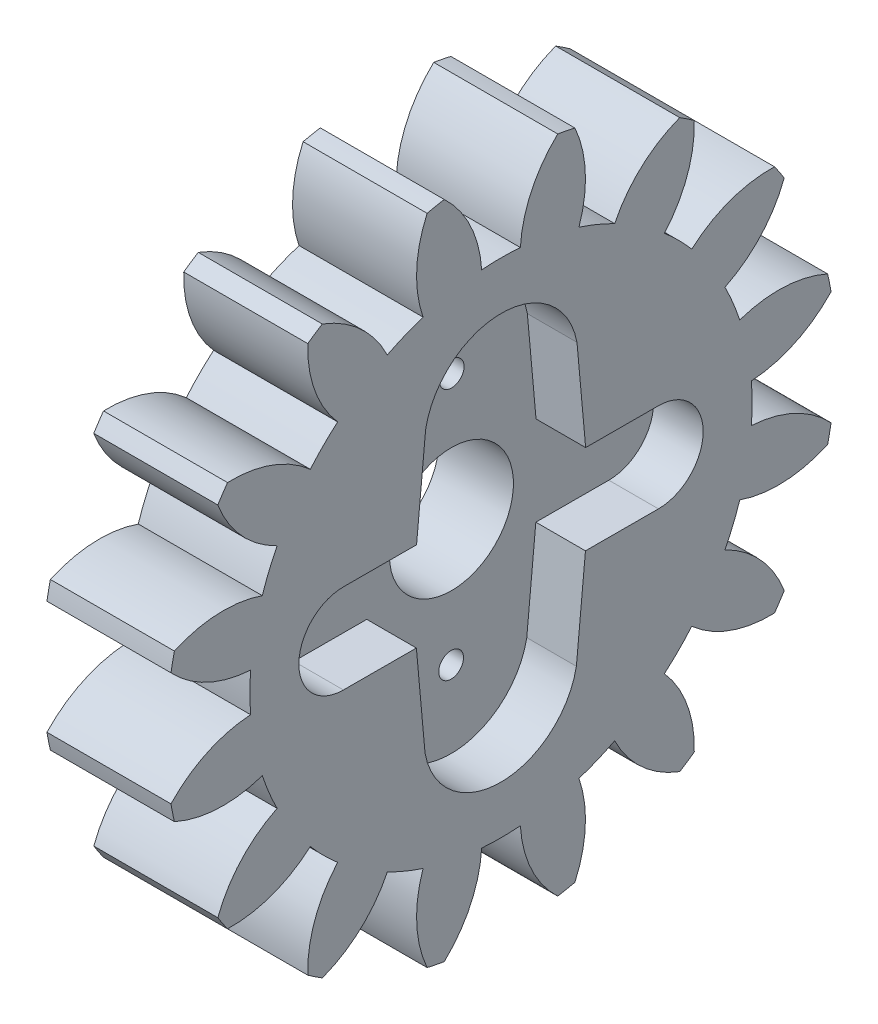
SolidWorks part; units mm, degrees
ref_plane "Plane1" through (0, 0, 0) normal (0, 0, 1) x (1, 0, 0)
ref_plane "Plane2" through (0, 0, 0) normal (0, 1, 0) x (1, 0, 0)
ref_plane "Plane3" through (0, 0, 0) normal (1, 0, 0) x (0, 0, -1)
other "Configuration Table"
sketch "HoldingSke" plane through (0, 0, 0) normal (0, 1, 0) x (1, 0, 0)
  line L0 (0, 0) -> (0.6408, -0.1838)
  line L1 (-15, 0) -> (100, 0) construction
  line L2 (0, 0) -> (-2.1039, 2.3779)
  line L3 (0, 0) -> (-11.863, 4.5341)
  line L4 (0, 0) -> (8.3015, 2.3804)
  line L5 (0, 0) -> (-46.8476, -17.4728)
  line L6 (0, 0) -> (-4.1448, -2.7965)
  line L7 (-2.1039, 2.3779) -> (8.6586, 51.2059)
  line L8 (-76.2, 54.61) -> (-75.3, 54.61)
  line L9 (-71.009, 38.7566) -> (-53.1078, 45.2721)
  line L10 (-76.2, 71.12) -> (104.1128, 71.12)
  line L11 (0, 0) -> (-5, 0)
  line L12 (-76.2, 101.6) -> (-76.147, 101.6)
  line L13 (24.9733, 27.94) -> (52.9518, 28.4284)
  line L14 (24.9733, 27.94) -> (24.9743, 27.94)
  line L15 (24.9733, 27.94) -> (100.4006, 29.5858)
  line L16 (-63.627, -1.5) -> (-12.827, -1.5)
  circle A0 centre (0, 0) radius 2.5
  circle A1 centre (0, 0) radius 10.124
  circle A2 centre (0, 0) radius 37.5
  circle A3 centre (0, 0) radius 2.5
  dimension "MHD" = 20.248
  dimension "Hub_dia" = 75
  dimension "Bore" = 5
  dimension "MBD" = 5
  dimension "Num_teeth" = 16
  dimension "Pitch" = 0.6667
  dimension "Overall_len" = 50
  dimension "Show_teeth" = 16
  dimension "Thickness" = 5
  dimension "OAL" = 50.0001
  dimension "T_dim" = 0.9
  dimension "Ap" = 20
  dimension "H" = 19.05
  dimension "Pitch_radius" = 180.3128
  dimension "Width" = 5
  dimension "Backlash" = 0.053
  dimension "Addendum_fac" = 1
  dimension "Dedendum_fac" = 1.25
  dimension "Clearance_fac" = 0.25
  dimension "Dedendum_add" = 0.001
  dimension "Module" = 1.5
sketch "BasProSke" plane through (0, 0, 0) normal (0, 1, 0) x (1, 0, 0)
  line L0 (-10, 0) -> (60, 0) construction
  line L1 (0, 0) -> (0, 13.5)
  line L2 (0, 0) -> (5, 0)
  line L3 (5, 0) -> (5, 13.5)
  line L4 (5, 13.5) -> (0, 13.5)
  dimension "Thickness" = 5
  dimension "Diameter" = 27
revolve "Base-Revolve" add sketch "BasProSke" angle 360 about L0
sketch "TooCutSke" plane through (0, 0, 0) normal (1, 0, 0) x (0, 0, -1)
  line L1 (0, 0) -> (0, 107) construction
  line L2 (0, 0) -> (-1.2689, 11.9327) construction
  line L3 (0, 0) -> (-4.663, 23.4427) construction
  line L4 (-1.2689, 11.9327) -> (-2.3315, 11.7214) construction
  arc A0 (0.7798, 10.0939) -> (-0.7798, 10.0939) centre (0, 0) ccw
  arc A1 (2.3105, 13.3266) -> (-2.3105, 13.3266) centre (0, 0) ccw
  circle A2 centre (0, 0) radius 12 construction
  circle A3 centre (0, 0) radius 11.2763 construction
  arc A4 (-0.7798, 10.0939) -> (-2.3105, 13.3266) centre (-5.571, 9.804) ccw
  arc A5 (2.3105, 13.3266) -> (0.7798, 10.0939) centre (5.571, 9.804) ccw
  dimension "Root_dia" = 20.248
  dimension "Overcut_dia" = 27.0508
  dimension "Pitch_dia" = 24
  dimension "Base_dia" = 22.5526
  dimension "Flank_rad" = 4.8
  dimension "Half_ang" = 11.25
  dimension "Half_CT" = 1.0835
extrude "ToothCut" cut sketch "TooCutSke" along normal through all
fillet "Breaks" [suppressed] radius 0.03
fillet "RootFillets" [suppressed] radius 0.376
pattern_circular "TeethCuts" count 16 every 22.5 about axis through (-10, 0, 0) along (1, 0, 0) of "ToothCut", "RootFillets", "Breaks"
sketch "HubNeaOneSke" plane through (0, 0, 0) normal (-1, 0, 0) x (0, 0, 1)
  circle A0 centre (0, 0) radius 10.124
  dimension "Diameter" = 20.248
extrude "HubNearOne" [suppressed] add sketch "HubNeaOneSke" along normal blind 45.0001
sketch "HubNeaBotSke" plane through (0, 0, 0) normal (-1, 0, 0) x (0, 0, 1)
  circle A0 centre (0, 0) radius 10.124
  dimension "Diameter" = 20.248
extrude "HubNearBoth" [suppressed] add sketch "HubNeaBotSke" along normal blind 22.5
ref_plane "FarPln" through (5, 0, 0) normal (1, 0, 0) x (0, 0, -1)
sketch "HubFarSke" plane through (5, 0, 0) normal (1, 0, 0) x (0, 0, -1)
  circle A0 centre (0, 0) radius 10.124
  dimension "Diameter" = 20.248
extrude "HubFar" [suppressed] add sketch "HubFarSke" along normal blind 22.5
sketch "BorSke" plane through (0, 0, 0) normal (1, 0, 0) x (0, 0, -1)
  circle A0 centre (0, 0) radius 2.5
  dimension "Diameter" = 5
extrude "Bore" cut sketch "BorSke" along normal mid plane 100.0001
sketch "KeySke" plane through (0, 0, 0) normal (1, 0, 0) x (0, 0, -1)
  line L0 (-1, 0) -> (-1, 3.4)
  line L1 (-1, 3.4) -> (1, 3.4)
  line L2 (1, 3.4) -> (1, 0)
  line L3 (0, 0) -> (0, 34) construction
  line L4 (-1, 0) -> (1, 0)
  dimension "Offset" = 3.4
  dimension "Width" = 2
extrude "Keyway" [suppressed] cut sketch "KeySke" along normal mid plane 100.0001
pattern_circular "Keyway2" [suppressed] count 2 every 90 about axis through (-10, 0, 0) along (1, 0, 0)
sketch "Esquisse1" plane through (5, 0, 0) normal (1, 0, 0) x (0, 0, -1)
  line L0 (-6.3538, -1.7865) -> (-3.4117, -1.7927) construction
  line L1 (-6.3538, -1.7865) -> (-3.4117, -1.7927)
  line L2 (-6.3462, 1.8135) -> (-3.404, 1.8073)
  line L3 (-3.4117, -1.7927) -> (-3.0624, -5.6432)
  line L4 (3.0384, -5.6562) -> (3.404, -1.8073)
  line L5 (3.404, -1.8073) -> (6.3462, -1.8135)
  line L6 (6.3538, 1.7865) -> (3.4117, 1.7927)
  line L7 (3.0624, 5.6432) -> (3.4117, 1.7927) construction
  line L8 (6.3538, 1.7865) -> (3.4117, 1.7927) construction
  line L9 (3.4117, 1.7927) -> (3.0624, 5.6432)
  line L10 (-3.404, 1.8073) -> (-3.0384, 5.6562)
  arc A0 (-6.3538, -1.7865) -> (-6.3462, 1.8135) centre (-6.35, 0.0135) cw
  arc A1 (-6.3462, 1.8135) -> (-6.3538, -1.7865) centre (-6.35, 0.0135) ccw construction
  arc A2 (-3.0624, -5.6432) -> (3.0384, -5.6562) centre (-0.0108, -5.0783) ccw
  arc A3 (6.3462, -1.8135) -> (6.3538, 1.7865) centre (6.35, -0.0135) ccw
  arc A4 (-3.0384, 5.6562) -> (3.0624, 5.6432) centre (0.0108, 5.0783) cw
extrude "Enlèv. mat.-Extru.1" cut sketch "Esquisse1" against normal blind 2
sketch "Esquisse2" plane through (3, 0, 0) normal (1, 0, 0) x (0, 0, -1)
  circle A0 centre (-0.0108, -5.0783) radius 0.5
  circle A1 centre (0.0108, 5.0783) radius 0.5
extrude "Enlèv. mat.-Extru.2" cut sketch "Esquisse2" against normal through all
equation "' \"Module@HoldingSke\" = 6.35"
equation "' \"Num_teeth@HoldingSke\" = 12"
equation "' \"Ap@HoldingSke\" =  20"
equation "' \"Ap@HoldingSke\" = 20"
equation "' \"Width@HoldingSke\" = 0.5 * 25.4"
equation "' \"Hub_dia@HoldingSke\"= 1 * 25.4"
equation "' \"Hub_dia@HoldingSke\" = 1 * 25.4"
equation "' \"Overall_len@HoldingSke\" = 1.0 * 25.4"
equation "' \"Bore@HoldingSke\" = 0.75 * 25.4"
equation "' \"T_dim@HoldingSke\" = 0.1 * 25.4"
equation "' \"Width@KeySke\" = 0.25 * 25.4"
equation "' \"Show_teeth@HoldingSke\" = 13"
equation "' \"Backlash@HoldingSke\" = 0.009 * 25.4"
equation "' \"Addendum_fac@HoldingSke\" = 1.0"
equation "' \"Dedendum_fac@HoldingSke\" = 1.25"
equation "' \"Dedendum_add@HoldingSke\" = 0.00005 * 25.4"
equation "' \"Clearance_fac@HoldingSke\" = 0.25"
equation "\"Pitch@HoldingSke\" = 1 / \"Module@HoldingSke\""
equation "\"Overcut_dia@TooCutSke\" = (\"Num_teeth@HoldingSke\" + 2 * \"Addendum_fac@HoldingSke\") / \"Pitch@HoldingSke\" + 0.002 * 25.4"
equation "\"Pitch_dia@TooCutSke\" = \"Num_teeth@HoldingSke\" / \"Pitch@HoldingSke\""
equation "\"Base_dia@TooCutSke\" = \"Num_teeth@HoldingSke\" / \"Pitch@HoldingSke\" * cos((\"Ap@HoldingSke\"  * 3.14159265 / 180))"
equation "\"Root_dia@TooCutSke\" = (\"Num_teeth@HoldingSke\" + 2) / \"Pitch@HoldingSke\" - 2 * (\"Addendum_fac@HoldingSke\" + \"Dedendum_fac@HoldingSke\") / \"Pitch@HoldingSke\" - \"Dedendum_add@HoldingSke\" * 2"
equation "\"Half_ang@TooCutSke\" = 180 / \"Num_teeth@HoldingSke\""
equation "\"Half_CT@TooCutSke\" = \"Num_teeth@HoldingSke\" / \"Pitch@HoldingSke\" * sin((3.14159265 / 2 / \"Num_teeth@HoldingSke\")) / 2 - 7 * \"Backlash@HoldingSke\" / 4"
equation "\"Flank_rad@TooCutSke\" = \"Num_teeth@HoldingSke\" / \"Pitch@HoldingSke\" / 5"
equation "\"Radius@RootFillets\" = \"Clearance_fac@HoldingSke\" / \"Pitch@HoldingSke\" + \"Dedendum_add@HoldingSke\""
equation "\"Break_rad@Breaks\" = 0.02 / \"Pitch@HoldingSke\""
equation "\"Thickness@HoldingSke\" = \"Width@HoldingSke\""
equation "\"OAL@HoldingSke\" = \"Thickness@HoldingSke\""
equation "\"MHD@HoldingSke\" = (\"Num_teeth@HoldingSke\" + 2) / \"Pitch@HoldingSke\" - 2 * (\"Addendum_fac@HoldingSke\" + \"Dedendum_fac@HoldingSke\")  / \"Pitch@HoldingSke\" - \"Dedendum_add@HoldingSke\" * 2"
equation "\"MBD@HoldingSke\" = (\"Num_teeth@HoldingSke\" + 2) / \"Pitch@HoldingSke\" - 2 * (\"Addendum_fac@HoldingSke\" + \"Dedendum_fac@HoldingSke\")  / \"Pitch@HoldingSke\" - \"Dedendum_add@HoldingSke\" * 2 - 0.002 * 25.4"
equation "\"MHD@HoldingSke\" = ((sgn( \"MHD@HoldingSke\" - \"Hub_dia@HoldingSke\" )-1)*( \"MHD@HoldingSke\" - \"Hub_dia@HoldingSke\" ))/-2+ \"Hub_dia@HoldingSke\""
equation "\"MBD@HoldingSke\" = ((sgn( \"MBD@HoldingSke\" - \"Bore@HoldingSke\" )-1)*( \"MBD@HoldingSke\" - \"Bore@HoldingSke\" ))/-2+ \"Bore@HoldingSke\""
equation "\"OAL@HoldingSke\" = ((sgn( \"OAL@HoldingSke\" - \"Overall_len@HoldingSke\" )+1)*( \"OAL@HoldingSke\" - \"Overall_len@HoldingSke\" ))/2 + \"Overall_len@HoldingSke\" + 0.000002 * 25.4"
equation "\"Num_teeth@TeethCuts\" = int( \"Show_teeth@HoldingSke\" ) + 1"
equation "\"Num_teeth@TeethCuts\" = ((sgn( \"Num_teeth@TeethCuts\" - \"Num_teeth@HoldingSke\" )-1)*( \"Num_teeth@TeethCuts\" - \"Num_teeth@HoldingSke\" ))/-2+ \"Num_teeth@HoldingSke\""
equation "\"Num_teeth@TeethCuts\" = ((sgn( \"Num_teeth@TeethCuts\" - 2.0)+1)*( \"Num_teeth@TeethCuts\" - 2.0))/2 +2.0"
equation "\"Angle@TeethCuts\" = 360.0 / \"Num_teeth@HoldingSke\""
equation "\"Diameter@BasProSke\" = (\"Num_teeth@HoldingSke\" + 2 * \"Addendum_fac@HoldingSke\") / \"Pitch@HoldingSke\""
equation "\"Thickness@BasProSke\"  = \"Thickness@HoldingSke\""
equation "' \"Fillet_rad@BasProSke\" =  \"Thickness@HoldingSke\" * 0.05"
equation "' \"Fillet_rad@BasProSke\" = \"Thickness@HoldingSke\" * 0.05"
equation "\"MHD@HoldingSke\" = ((sgn( \"MHD@HoldingSke\" - \"Root_dia@TooCutSke\" )-1)*( \"MHD@HoldingSke\" - \"Root_dia@TooCutSke\" ))/-2+ \"Root_dia@TooCutSke\""
equation "\"Diameter@HubNeaOneSke\" = \"MHD@HoldingSke\""
equation "\"Length@HubNearOne\" = \"OAL@HoldingSke\" - \"Thickness@BasProSke\""
equation "\"Diameter@HubNeaBotSke\" = \"MHD@HoldingSke\""
equation "\"Length@HubNearBoth\" = ( \"OAL@HoldingSke\" - \"Thickness@BasProSke\" ) / 2.0"
equation "\"Thickness@FarPln\" = \"Thickness@BasProSke\""
equation "\"Diameter@HubFarSke\" = \"MHD@HoldingSke\""
equation "\"Length@HubFar\" = ( \"OAL@HoldingSke\" - \"Thickness@BasProSke\" ) / 2.0"
equation "\"Diameter@BorSke\" = \"MBD@HoldingSke\""
equation "\"D1@Bore\" = \"OAL@HoldingSke\" * 2.0"
equation "\"D1@Keyway\" = \"OAL@HoldingSke\" * 2.0"
equation "\"Offset@KeySke\" = \"T_dim@HoldingSke\" + \"MBD@HoldingSke\" / 2.0"
